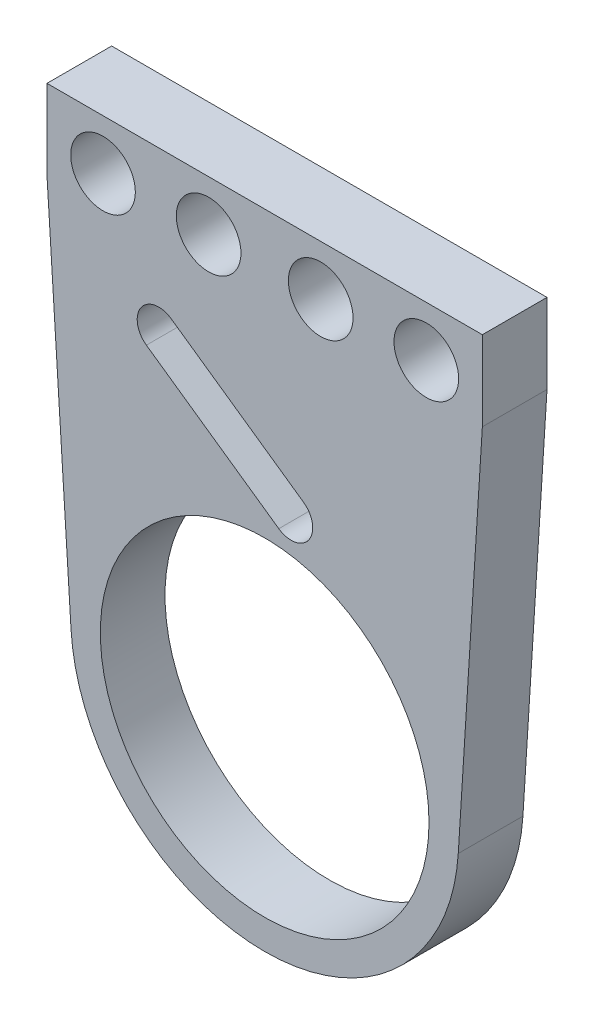
SolidWorks part; units mm, degrees
material "Foam"
ref_plane "Front Plane" through (0, 0, 0) normal (0, 0, 1) x (1, 0, 0)
ref_plane "Top Plane" through (0, 0, 0) normal (0, 1, 0) x (1, 0, 0)
ref_plane "Right Plane" through (0, 0, 0) normal (1, 0, 0) x (0, 0, -1)
sketch "Sketch1" plane through (0, 0, 0) normal (0, 0, 1) x (1, 0, 0)
  line L0 (0, 83.4741) -> (0, 41.6741) construction
  line L1 (0, 41.6741) -> (20.2, 41.6741)
  line L2 (20.2, 41.6741) -> (20.2, 83.4741) construction
  line L3 (20.2, 83.4741) -> (0, 83.4741) construction
  line L4 (10.1, 83.4741) -> (10.1, 41.6741) construction
  line L5 (10.1, 62.5741) -> (20.2, 62.5741) construction
  line L6 (-20.2, 83.4741) -> (-20.2, 41.6741) construction
  line L7 (-20.2, 41.6741) -> (0, 41.6741)
  line L8 (0, 0) -> (0, 90.8741) construction
  line L9 (0, 83.4741) -> (-20.2, 83.4741) construction
  line L10 (-10.1, 83.4741) -> (-10.1, 41.6741) construction
  line L11 (-20.2, 62.5741) -> (-10.1, 62.5741) construction
  line L12 (-20.2, 34.2741) -> (-17.9642, -1.1343)
  line L13 (20.2, 34.2741) -> (17.9642, -1.1343)
  line L14 (-20.2, 34.2741) -> (20.2, 34.2741) construction
  line L15 (-20.2, 41.6741) -> (-20.2, 34.2741)
  line L16 (20.2, 41.6741) -> (20.2, 34.2741)
  circle A0 centre (10.1, 73.3741) radius 6.5 construction
  arc A1 (-17.9642, -1.1343) -> (17.9642, -1.1343) centre (0, 0) cw construction
  circle A2 centre (0, 0) radius 7.95
  arc A3 (-17.9642, -1.1343) -> (17.9642, -1.1343) centre (0, 0) ccw
  circle A4 centre (5.2, 88.1241) radius 3 construction
  circle A5 centre (15, 88.1241) radius 3 construction
  circle A6 centre (-10.1, 51.7741) radius 6.5 construction
  circle A7 centre (-15, 88.1241) radius 3 construction
  circle A8 centre (-5.2, 88.1241) radius 3 construction
  circle A9 centre (-15, 37.0241) radius 3
  circle A10 centre (-5.2, 37.0241) radius 3
  circle A11 centre (0, 0) radius 52.75 construction
  circle A12 centre (5.2, 37.0241) radius 3
  circle A13 centre (15, 37.0241) radius 3
  dimension "D1" = 15.9
  dimension "D2" = 51.1
  dimension "D10" = 10.1
  dimension "D3" = 18
  dimension "D14" = 105.5
  dimension "D16" = 9.8
  dimension "D6" = 10.1
  dimension "D7" = 13
  dimension "D8" = 6
  dimension "D9" = 20.2
  dimension "D11" = 41.8
  dimension "D12" = 9.8
  dimension "D18" = 7.4
  dimension "D19" = 7.4
extrude "Main Body Link B2" add sketch "Sketch1" along normal blind 6
sketch "Sketch2" plane through (0, 0, 6) normal (0, 0, 1) x (1, 0, 0)
  line L0 (0, -7.95) -> (0, 7.95) construction
  circle A0 centre (-11.5, 0) radius 1.5
  circle A1 centre (11.5, 0) radius 1.5
  circle A2 centre (0, 0) radius 7.95 construction
  dimension "D1" = 3
  dimension "D2" = 11.5
extrude "Cut-Extrude1" cut sketch "Sketch2" against normal up to next
sketch "Sketch3" plane through (0, 0, 6) normal (0, 0, 1) x (1, 0, 0)
  line L0 (0, 0) -> (0, 20) construction
  line L1 (-9.8298, 26.8829) -> (2.4575, 18.2793) construction
  line L2 (-8.6827, 28.5212) -> (3.6046, 19.9176)
  line L3 (-10.977, 25.2446) -> (1.3103, 16.641)
  arc A0 (-8.6827, 28.5212) -> (-10.977, 25.2446) centre (-9.8298, 26.8829) ccw
  arc A1 (1.3103, 16.641) -> (3.6046, 19.9176) centre (2.4575, 18.2793) ccw
  dimension "D5" = 4
  dimension "D1" = 55
  dimension "D2" = 3
  dimension "D3" = 12
  dimension "D4" = 20
extrude "Cut-Extrude2" cut sketch "Sketch3" against normal through all
sketch "Sketch4" plane through (0, 0, 6) normal (0, 0, 1) x (1, 0, 0)
  circle A0 centre (0, 0) radius 15.25
  dimension "D1" = 30.5
extrude "Cut-Extrude3" cut sketch "Sketch4" against normal through all
equation "\"D1@Sketch1\"=16.00mm-\"radii_fit@Parameters@Parameters.SLDPRT\""
equation "\"D14@Sketch1\"=\"CenterDist2@Parameters@Parameters.SLDPRT\"*2"
